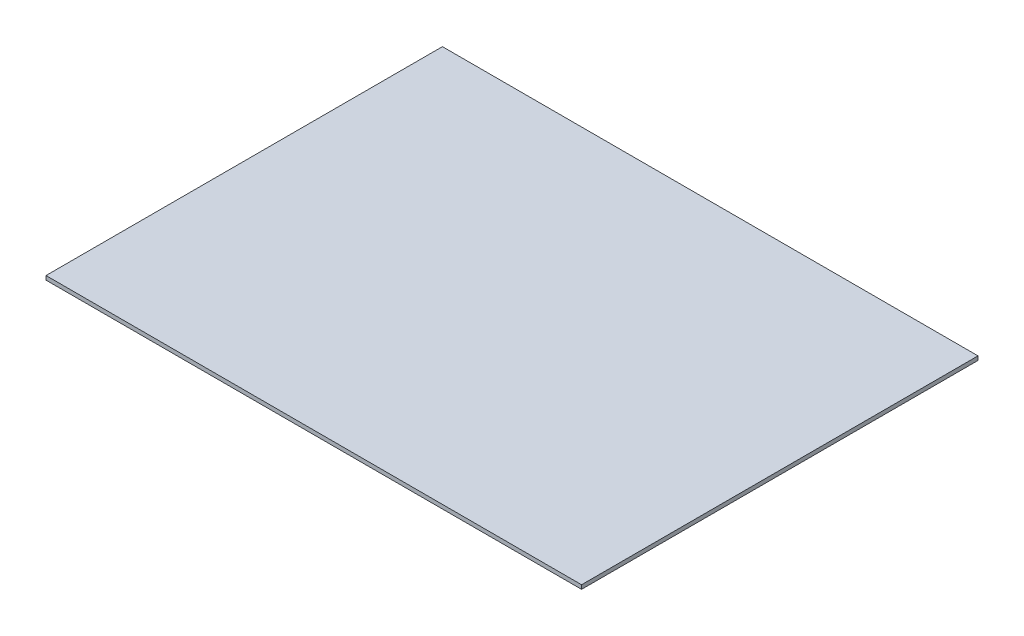
SolidWorks part; units mm, degrees
material "Akryl (středně-vysoký dopad)"
ref_plane "Přední rovina" through (0, 0, 0) normal (0, 0, 1) x (1, 0, 0)
ref_plane "Horní rovina" through (0, 0, 0) normal (0, 1, 0) x (1, 0, 0)
ref_plane "Pravá rovina" through (0, 0, 0) normal (1, 0, 0) x (0, 0, -1)
sketch "Skica1" plane through (0, 0, 0) normal (0, 1, 0) x (1, 0, 0)
  line L1 (267.5, -198) -> (-267.5, -198)
  line L2 (267.5, -198) -> (267.5, 198)
  line L3 (267.5, 198) -> (-267.5, 198)
  line L4 (-267.5, -198) -> (-267.5, 198)
  line L5 (267.5, -198) -> (-267.5, 198) construction
  line L6 (267.5, 198) -> (-267.5, -198) construction
  point P0 (0, 0)
  dimension "D1" = 535
  dimension "D2" = 396
extrude "Přidat vysunutím1" add sketch "Skica1" along normal blind 4
